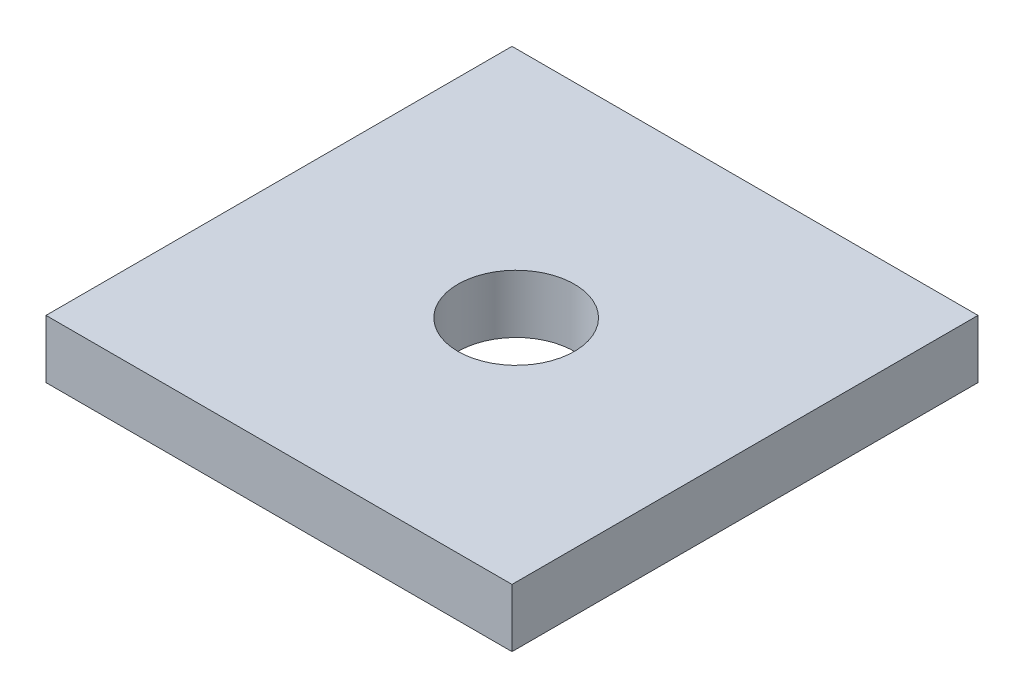
SolidWorks part; units mm, degrees
ref_plane "Front Plane" through (0, 0, 0) normal (0, 0, 1) x (1, 0, 0)
ref_plane "Top Plane" through (0, 0, 0) normal (0, 1, 0) x (1, 0, 0)
ref_plane "Right Plane" through (0, 0, 0) normal (1, 0, 0) x (0, 0, -1)
sketch "Sketch1" plane through (0, 0, 0) normal (0, 1, 0) x (1, 0, 0)
  line L1 (0, 0) -> (25.4, 0)
  line L2 (0, 0) -> (0, 25.4)
  line L3 (0, 25.4) -> (25.4, 25.4)
  line L4 (25.4, 0) -> (25.4, 25.4)
  point P5 (25.4, 21.4237)
  dimension "D1" = 25.4
  dimension "D2" = 25.4
extrude "Boss-Extrude1" add sketch "Sketch1" along normal blind 3.175
sketch "Sketch2" plane through (0, 3.175, 0) normal (0, 1, 0) x (1, 0, 0)
  circle A0 centre (12.9276, 12.7) radius 3.175
  point P2 (12.9276, 12.7)
  dimension "D1" = 6.35
extrude "Cut-Extrude1" cut sketch "Sketch2" against normal through all
